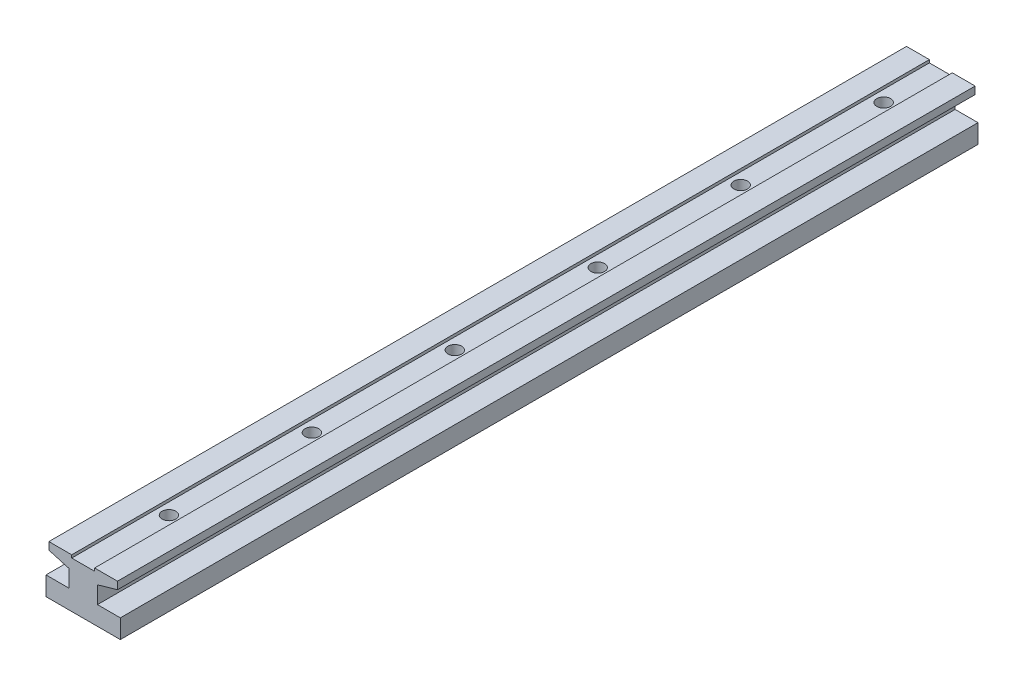
SolidWorks part; units mm, degrees
ref_plane "Ebene vorne" through (0, 0, 0) normal (0, 0, 1) x (1, 0, 0)
ref_plane "Ebene oben" through (0, 0, 0) normal (0, 1, 0) x (1, 0, 0)
ref_plane "Ebene rechts" through (0, 0, 0) normal (1, 0, 0) x (0, 0, -1)
sketch "Skizze1" plane through (0, 0, 0) normal (0, 0, 1) x (1, 0, 0)
  line L2 (0, 0) -> (-6.5, 0)
  line L3 (-6.5, 0) -> (-6.5, 3.3)
  line L4 (-6.5, 3.3) -> (-2.5, 3.3)
  line L5 (-2.5, 3.3) -> (-2.5, 6.3)
  line L6 (-2.5, 6.3) -> (-6, 7.3)
  line L7 (-6, 7.3) -> (-6, 8.6)
  line L8 (-6, 8.6) -> (-2, 8.6)
  line L9 (-2, 8.6) -> (-2, 8.1)
  line L10 (-2, 8.1) -> (2, 8.1)
  line L11 (0, 8.1) -> (0, 0) construction
  line L12 (2, 8.6) -> (2, 8.1)
  line L13 (6, 8.6) -> (2, 8.6)
  line L14 (6, 7.3) -> (6, 8.6)
  line L15 (2.5, 6.3) -> (6, 7.3)
  line L16 (2.5, 3.3) -> (2.5, 6.3)
  line L17 (6.5, 3.3) -> (2.5, 3.3)
  line L18 (6.5, 0) -> (6.5, 3.3)
  line L19 (0, 0) -> (6.5, 0)
  point P23 (-2.5, 4.8)
  dimension "D1" = 13
  dimension "D2" = 8.6
  dimension "D3" = 3.3
  dimension "D4" = 5
  dimension "D5" = 12
  dimension "D7" = 0.5
  dimension "D9" = 1.3
  dimension "D10" = 3
  dimension "D11" = 4
extrude "Aufsatz-Linear austragen1" add sketch "Skizze1" along normal blind 150
hole_wizard "Stirnsenkung für M2 Flachkopfschraube mit Schlitz1" positions "Skizze6" profile "Skizze7" counterbore size "M2" standard "DIN" end condition through all
sketch "Skizze6" plane through (0, 0, 0) normal (0, -1, 0) x (-1, 0, 0)
  point P0 (0, -85)
  point P2 (0, -60)
  point P7 (0, -35)
  point P11 (0, -10)
  point P12 (0, -110)
  point P14 (0, -135)
  dimension "D1" = 25
  dimension "D2" = 25
  dimension "D3" = 25
  dimension "D4" = 25
  dimension "D5" = 25
  dimension "D6" = 10
sketch "Skizze7" plane through (0, 0, 85) normal (1, 0, 0) x (0, 0, -1)
  line L0 (0, 0) -> (0, 8.6)
  line L1 (0, 8.6) -> (1.2, 8.6)
  line L3 (1.2, 8.6) -> (1.2, 1.6)
  line L4 (1.2, 1.6) -> (2.5, 1.6)
  line L5 (2.5, 1.6) -> (2.5, 0)
  line L7 (2.5, 0) -> (0, 0)
  line L11 (0, -6.35) -> (0, 107.95) construction
  dimension "Bohrerdurchmesser" = 2.4
  dimension "Bohrungstiefe" = 8.6
  dimension "Senkdurchmesser2" = 5
  dimension "Senktiefe2" = 1.6
